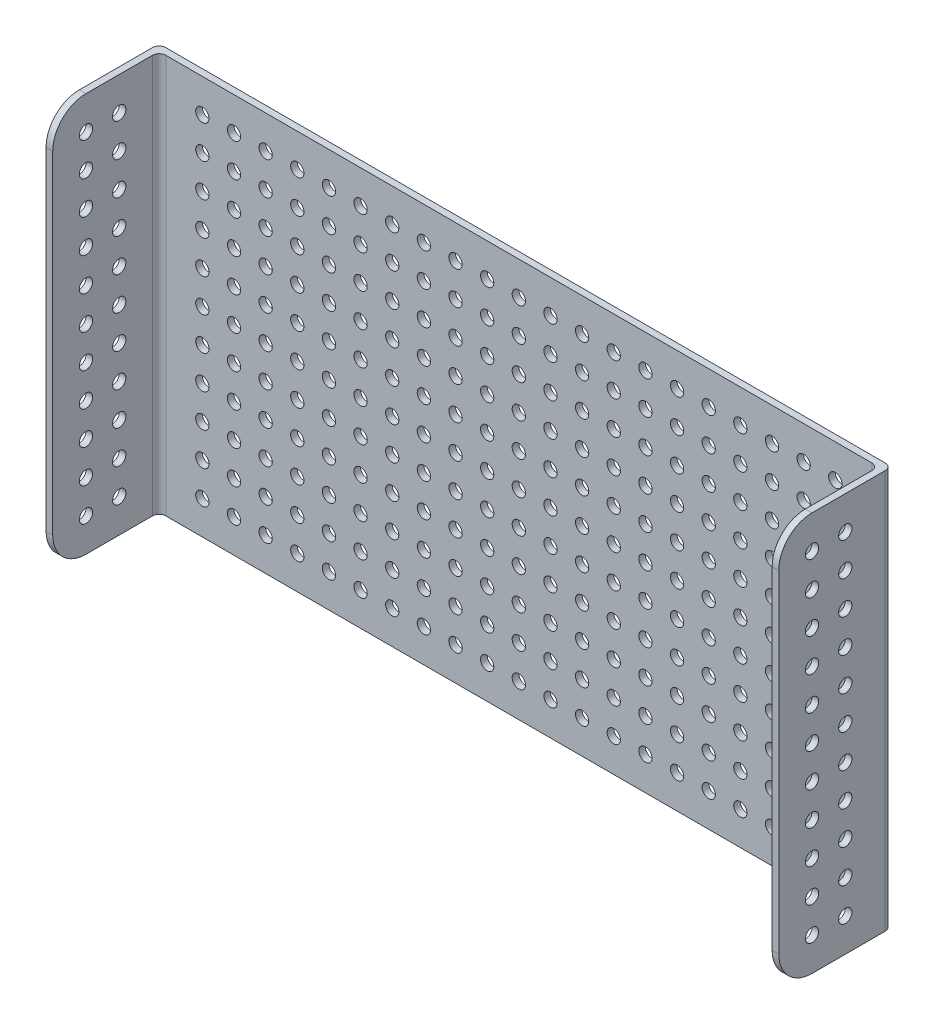
SolidWorks part; units mm, degrees
material "6061-T6 (SS)"
ref_plane "Ön Düzlem" through (0, 0, 0) normal (0, 0, 1) x (1, 0, 0)
ref_plane "Üst Düzlem" through (0, 0, 0) normal (0, 1, 0) x (1, 0, 0)
ref_plane "Sağ Düzlem" through (0, 0, 0) normal (1, 0, 0) x (0, 0, -1)
sketch "Çizim1" plane through (0, 0, 0) normal (0, 0, 1) x (1, 0, 0)
  line L0 (-110.2, -60) -> (110.2, 60) construction
  line L1 (-110.2, 60) -> (110.2, 60)
  line L2 (-110.2, 60) -> (-110.2, -60)
  line L3 (-110.2, -60) -> (110.2, -60)
  line L4 (110.2, 60) -> (110.2, -60)
  line L5 (-66.64, 0) -> (-76.16, 0) construction
  line L6 (95.2, 50) -> (95.2, 40) construction
  line L8 (85.68, 50) -> (95.2, 50) construction
  circle A0 centre (95.2, 50) radius 2
  circle A1 centre (85.68, 50) radius 2
  circle A2 centre (76.16, 50) radius 2
  circle A3 centre (66.64, 50) radius 2
  circle A4 centre (57.12, 50) radius 2
  circle A5 centre (47.6, 50) radius 2
  circle A6 centre (38.08, 50) radius 2
  circle A7 centre (28.56, 50) radius 2
  circle A8 centre (19.04, 50) radius 2
  circle A9 centre (9.52, 50) radius 2
  circle A10 centre (0, 50) radius 2
  circle A11 centre (-9.52, 50) radius 2
  circle A12 centre (-19.04, 50) radius 2
  circle A13 centre (-28.56, 50) radius 2
  circle A14 centre (-38.08, 50) radius 2
  circle A15 centre (-47.6, 50) radius 2
  circle A16 centre (-57.12, 50) radius 2
  circle A17 centre (-66.64, 50) radius 2
  circle A18 centre (-76.16, 50) radius 2
  circle A19 centre (-85.68, 50) radius 2
  circle A20 centre (-95.2, 50) radius 2
  circle A36 centre (85.68, 40) radius 2
  circle A37 centre (76.16, 40) radius 2
  circle A38 centre (66.64, 40) radius 2
  circle A39 centre (57.12, 40) radius 2
  circle A40 centre (47.6, 40) radius 2
  circle A41 centre (38.08, 40) radius 2
  circle A42 centre (28.56, 40) radius 2
  circle A43 centre (19.04, 40) radius 2
  circle A44 centre (9.52, 40) radius 2
  circle A45 centre (0, 40) radius 2
  circle A46 centre (-9.52, 40) radius 2
  circle A47 centre (-19.04, 40) radius 2
  circle A48 centre (-28.56, 40) radius 2
  circle A49 centre (-38.08, 40) radius 2
  circle A50 centre (-47.6, 40) radius 2
  circle A51 centre (-57.12, 40) radius 2
  circle A52 centre (-66.64, 40) radius 2
  circle A53 centre (-76.16, 40) radius 2
  circle A54 centre (-85.68, 40) radius 2
  circle A55 centre (-95.2, 40) radius 2
  circle A71 centre (85.68, 30) radius 2
  circle A72 centre (76.16, 30) radius 2
  circle A73 centre (66.64, 30) radius 2
  circle A74 centre (57.12, 30) radius 2
  circle A75 centre (47.6, 30) radius 2
  circle A76 centre (38.08, 30) radius 2
  circle A77 centre (28.56, 30) radius 2
  circle A78 centre (19.04, 30) radius 2
  circle A79 centre (9.52, 30) radius 2
  circle A80 centre (0, 30) radius 2
  circle A81 centre (-9.52, 30) radius 2
  circle A82 centre (-19.04, 30) radius 2
  circle A83 centre (-28.56, 30) radius 2
  circle A84 centre (-38.08, 30) radius 2
  circle A85 centre (-47.6, 30) radius 2
  circle A86 centre (-57.12, 30) radius 2
  circle A87 centre (-66.64, 30) radius 2
  circle A88 centre (-76.16, 30) radius 2
  circle A89 centre (-85.68, 30) radius 2
  circle A90 centre (-95.2, 30) radius 2
  circle A106 centre (85.68, 20) radius 2
  circle A107 centre (76.16, 20) radius 2
  circle A108 centre (66.64, 20) radius 2
  circle A109 centre (57.12, 20) radius 2
  circle A110 centre (47.6, 20) radius 2
  circle A111 centre (38.08, 20) radius 2
  circle A112 centre (28.56, 20) radius 2
  circle A113 centre (19.04, 20) radius 2
  circle A114 centre (9.52, 20) radius 2
  circle A115 centre (0, 20) radius 2
  circle A116 centre (-9.52, 20) radius 2
  circle A117 centre (-19.04, 20) radius 2
  circle A118 centre (-28.56, 20) radius 2
  circle A119 centre (-38.08, 20) radius 2
  circle A120 centre (-47.6, 20) radius 2
  circle A121 centre (-57.12, 20) radius 2
  circle A122 centre (-66.64, 20) radius 2
  circle A123 centre (-76.16, 20) radius 2
  circle A124 centre (-85.68, 20) radius 2
  circle A125 centre (-95.2, 20) radius 2
  circle A141 centre (85.68, 10) radius 2
  circle A142 centre (76.16, 10) radius 2
  circle A143 centre (66.64, 10) radius 2
  circle A144 centre (57.12, 10) radius 2
  circle A145 centre (47.6, 10) radius 2
  circle A146 centre (38.08, 10) radius 2
  circle A147 centre (28.56, 10) radius 2
  circle A148 centre (19.04, 10) radius 2
  circle A149 centre (9.52, 10) radius 2
  circle A150 centre (0, 10) radius 2
  circle A151 centre (-9.52, 10) radius 2
  circle A152 centre (-19.04, 10) radius 2
  circle A153 centre (-28.56, 10) radius 2
  circle A154 centre (-38.08, 10) radius 2
  circle A155 centre (-47.6, 10) radius 2
  circle A156 centre (-57.12, 10) radius 2
  circle A157 centre (-66.64, 10) radius 2
  circle A158 centre (-76.16, 10) radius 2
  circle A159 centre (-85.68, 10) radius 2
  circle A160 centre (-95.2, 10) radius 2
  circle A176 centre (85.68, 0) radius 2
  circle A177 centre (76.16, 0) radius 2
  circle A178 centre (66.64, 0) radius 2
  circle A179 centre (57.12, 0) radius 2
  circle A180 centre (47.6, 0) radius 2
  circle A181 centre (38.08, 0) radius 2
  circle A182 centre (28.56, 0) radius 2
  circle A183 centre (19.04, 0) radius 2
  circle A184 centre (9.52, 0) radius 2
  circle A185 centre (0, 0) radius 2
  circle A186 centre (-9.52, 0) radius 2
  circle A187 centre (-19.04, 0) radius 2
  circle A188 centre (-28.56, 0) radius 2
  circle A189 centre (-38.08, 0) radius 2
  circle A190 centre (-47.6, 0) radius 2
  circle A191 centre (-57.12, 0) radius 2
  circle A192 centre (-66.64, 0) radius 2
  circle A193 centre (-76.16, 0) radius 2
  circle A194 centre (-85.68, 0) radius 2
  circle A195 centre (-95.2, 0) radius 2
  circle A211 centre (85.68, -10) radius 2
  circle A212 centre (76.16, -10) radius 2
  circle A213 centre (66.64, -10) radius 2
  circle A214 centre (57.12, -10) radius 2
  circle A215 centre (47.6, -10) radius 2
  circle A216 centre (38.08, -10) radius 2
  circle A217 centre (28.56, -10) radius 2
  circle A218 centre (19.04, -10) radius 2
  circle A219 centre (9.52, -10) radius 2
  circle A220 centre (0, -10) radius 2
  circle A221 centre (-9.52, -10) radius 2
  circle A222 centre (-19.04, -10) radius 2
  circle A223 centre (-28.56, -10) radius 2
  circle A224 centre (-38.08, -10) radius 2
  circle A225 centre (-47.6, -10) radius 2
  circle A226 centre (-57.12, -10) radius 2
  circle A227 centre (-66.64, -10) radius 2
  circle A228 centre (-76.16, -10) radius 2
  circle A229 centre (-85.68, -10) radius 2
  circle A230 centre (-95.2, -10) radius 2
  circle A246 centre (85.68, -20) radius 2
  circle A247 centre (76.16, -20) radius 2
  circle A248 centre (66.64, -20) radius 2
  circle A249 centre (57.12, -20) radius 2
  circle A250 centre (47.6, -20) radius 2
  circle A251 centre (38.08, -20) radius 2
  circle A252 centre (28.56, -20) radius 2
  circle A253 centre (19.04, -20) radius 2
  circle A254 centre (9.52, -20) radius 2
  circle A255 centre (0, -20) radius 2
  circle A256 centre (-9.52, -20) radius 2
  circle A257 centre (-19.04, -20) radius 2
  circle A258 centre (-28.56, -20) radius 2
  circle A259 centre (-38.08, -20) radius 2
  circle A260 centre (-47.6, -20) radius 2
  circle A261 centre (-57.12, -20) radius 2
  circle A262 centre (-66.64, -20) radius 2
  circle A263 centre (-76.16, -20) radius 2
  circle A264 centre (-85.68, -20) radius 2
  circle A265 centre (-95.2, -20) radius 2
  circle A281 centre (85.68, -30) radius 2
  circle A282 centre (76.16, -30) radius 2
  circle A283 centre (66.64, -30) radius 2
  circle A284 centre (57.12, -30) radius 2
  circle A285 centre (47.6, -30) radius 2
  circle A286 centre (38.08, -30) radius 2
  circle A287 centre (28.56, -30) radius 2
  circle A288 centre (19.04, -30) radius 2
  circle A289 centre (9.52, -30) radius 2
  circle A290 centre (0, -30) radius 2
  circle A291 centre (-9.52, -30) radius 2
  circle A292 centre (-19.04, -30) radius 2
  circle A293 centre (-28.56, -30) radius 2
  circle A294 centre (-38.08, -30) radius 2
  circle A295 centre (-47.6, -30) radius 2
  circle A296 centre (-57.12, -30) radius 2
  circle A297 centre (-66.64, -30) radius 2
  circle A298 centre (-76.16, -30) radius 2
  circle A299 centre (-85.68, -30) radius 2
  circle A300 centre (-95.2, -30) radius 2
  circle A316 centre (85.68, -40) radius 2
  circle A317 centre (76.16, -40) radius 2
  circle A318 centre (66.64, -40) radius 2
  circle A319 centre (57.12, -40) radius 2
  circle A320 centre (47.6, -40) radius 2
  circle A321 centre (38.08, -40) radius 2
  circle A322 centre (28.56, -40) radius 2
  circle A323 centre (19.04, -40) radius 2
  circle A324 centre (9.52, -40) radius 2
  circle A325 centre (0, -40) radius 2
  circle A326 centre (-9.52, -40) radius 2
  circle A327 centre (-19.04, -40) radius 2
  circle A328 centre (-28.56, -40) radius 2
  circle A329 centre (-38.08, -40) radius 2
  circle A330 centre (-47.6, -40) radius 2
  circle A331 centre (-57.12, -40) radius 2
  circle A332 centre (-66.64, -40) radius 2
  circle A333 centre (-76.16, -40) radius 2
  circle A334 centre (-85.68, -40) radius 2
  circle A335 centre (-95.2, -40) radius 2
  circle A351 centre (85.68, -50) radius 2
  circle A352 centre (76.16, -50) radius 2
  circle A353 centre (66.64, -50) radius 2
  circle A354 centre (57.12, -50) radius 2
  circle A355 centre (47.6, -50) radius 2
  circle A356 centre (38.08, -50) radius 2
  circle A357 centre (28.56, -50) radius 2
  circle A358 centre (19.04, -50) radius 2
  circle A359 centre (9.52, -50) radius 2
  circle A360 centre (0, -50) radius 2
  circle A361 centre (-9.52, -50) radius 2
  circle A362 centre (-19.04, -50) radius 2
  circle A363 centre (-28.56, -50) radius 2
  circle A364 centre (-38.08, -50) radius 2
  circle A365 centre (-47.6, -50) radius 2
  circle A366 centre (-57.12, -50) radius 2
  circle A367 centre (-66.64, -50) radius 2
  circle A368 centre (-76.16, -50) radius 2
  circle A369 centre (-85.68, -50) radius 2
  circle A370 centre (-95.2, -50) radius 2
  circle A386 centre (95.2, 40) radius 2
  circle A387 centre (95.2, 30) radius 2
  circle A388 centre (95.2, 20) radius 2
  circle A389 centre (95.2, 10) radius 2
  circle A390 centre (95.2, 0) radius 2
  circle A391 centre (95.2, -10) radius 2
  circle A392 centre (95.2, -20) radius 2
  circle A393 centre (95.2, -30) radius 2
  circle A394 centre (95.2, -40) radius 2
  circle A395 centre (95.2, -50) radius 2
  point P7 (-96.0586, 50)
  point P8 (-95.476, 50)
  dimension "D3" = 4
  dimension "D1" = 220.4
  dimension "D2" = 120
  dimension "D4" = 10
  dimension "D5" = 15
  dimension "D8" = 15
  dimension "D9" = 10
  dimension "D6" = 21
  dimension "D7" = 11
extrude "Yükseklik-Ekstrüzyon1" add sketch "Çizim1" along normal blind 2
sketch "Çizim3" plane through (0, 0, 2) normal (0, 0, 1) x (1, 0, 0)
  line L0 (-110.2, -60) -> (110.2, -60) construction
  line L1 (-110.2, 60) -> (-108.2, 60)
  line L2 (-110.2, 60) -> (-110.2, -60)
  line L3 (-110.2, -60) -> (-108.2, -60)
  line L4 (-108.2, 60) -> (-108.2, -60)
  line L5 (110.2, 60) -> (-110.2, 60) construction
  line L6 (108.2, 60) -> (110.2, 60)
  line L7 (108.2, 60) -> (108.2, -60)
  line L8 (108.2, -60) -> (110.2, -60)
  line L9 (110.2, 60) -> (110.2, -60)
  dimension "D1" = 2
  dimension "D2" = 2
extrude "Top Holes" add sketch "Çizim3" along normal blind 32
sketch "Çizim4" plane through (-110.2, 0, 0) normal (-1, 0, 0) x (0, 0, 1)
  line L0 (34, -60) -> (0, -60) construction
  line L1 (34, 60) -> (34, -60) construction
  circle A0 centre (14, -50) radius 2
  circle A1 centre (24, -50) radius 2
  circle A2 centre (24, -40) radius 2
  circle A3 centre (24, -30) radius 2
  circle A4 centre (24, -20) radius 2
  circle A5 centre (24, -10) radius 2
  circle A6 centre (24, 0) radius 2
  circle A7 centre (24, 10) radius 2
  circle A8 centre (24, 20) radius 2
  circle A9 centre (24, 30) radius 2
  circle A10 centre (24, 40) radius 2
  circle A11 centre (24, 50) radius 2
  circle A12 centre (14, -40) radius 2
  circle A13 centre (14, -30) radius 2
  circle A14 centre (14, -20) radius 2
  circle A15 centre (14, -10) radius 2
  circle A16 centre (14, 0) radius 2
  circle A17 centre (14, 10) radius 2
  circle A18 centre (14, 20) radius 2
  circle A19 centre (14, 30) radius 2
  circle A20 centre (14, 40) radius 2
  circle A21 centre (14, 50) radius 2
  dimension "D1" = 4
  dimension "D2" = 10
  dimension "D5" = 10
  dimension "D3" = 2
  dimension "D4" = 11
extrude "Kes-Ekstrüzyon1" cut sketch "Çizim4" against normal through all
fillet "Radyus1" radius 2 4 edges at (-108.2, 0, 2) (110.2, 0, 0) (108.2, 0, 2) (-110.2, 0, 0)
fillet "Radyus2" radius 10 4 edges at (-109.2, -60, 34) (-109.2, 60, 34) (109.2, 60, 34) (109.2, -60, 34)
equation "\"D8@Çizim1\"=\"D5@Çizim1\""
equation "\"D9@Çizim1\"=\"D4@Çizim1\""
